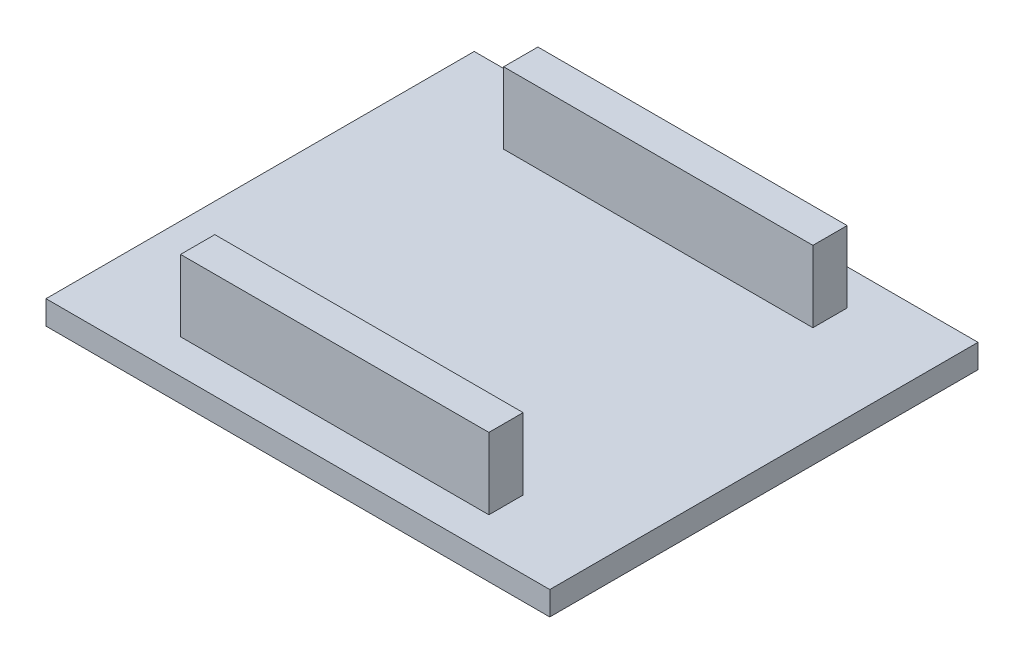
SolidWorks part; units mm, degrees
ref_plane "Front Plane" through (0, 0, 0) normal (0, 0, 1) x (1, 0, 0)
ref_plane "Top Plane" through (0, 0, 0) normal (0, 1, 0) x (1, 0, 0)
ref_plane "Right Plane" through (0, 0, 0) normal (1, 0, 0) x (0, 0, -1)
sketch "Sketch1" plane through (0, 0, 0) normal (0, 1, 0) x (1, 0, 0)
  line L1 (0, 0) -> (33.6176, 0)
  line L2 (0, 0) -> (0, 28.575)
  line L3 (0, 28.575) -> (33.6176, 28.575)
  line L4 (33.6176, 0) -> (33.6176, 28.575)
  dimension "D1" = 33.6176
  dimension "D2" = 28.575
extrude "Boss-Extrude1" add sketch "Sketch1" along normal blind 1.5875
sketch "Sketch2" plane through (0, 1.5875, 0) normal (0, 1, 0) x (1, 0, 0)
  line L0 (33.6176, 28.575) -> (0, 28.575) construction
  line L1 (6.6936, 2.286) -> (27.2676, 2.286)
  line L2 (6.6936, 2.286) -> (6.6936, 4.572)
  line L3 (6.6936, 4.572) -> (27.2676, 4.572)
  line L4 (27.2676, 2.286) -> (27.2676, 4.572)
  line L5 (6.6301, 23.9078) -> (27.2676, 23.9078)
  line L6 (6.6301, 23.9078) -> (6.6301, 26.1937)
  line L7 (6.6301, 26.1937) -> (27.2676, 26.1937)
  line L8 (27.2676, 23.9078) -> (27.2676, 26.1937)
  line L9 (33.6176, 0) -> (33.6176, 28.575) construction
  line L10 (0, 0) -> (33.6176, 0) construction
  dimension "D1" = 2.3813
  dimension "D2" = 2.286
  dimension "D3" = 6.35
  dimension "D4" = 20.6375
  dimension "D5" = 2.286
  dimension "D6" = 20.574
  dimension "D7" = 6.35
  dimension "D8" = 2.286
extrude "Boss-Extrude2" add sketch "Sketch2" along normal blind 4.7625
